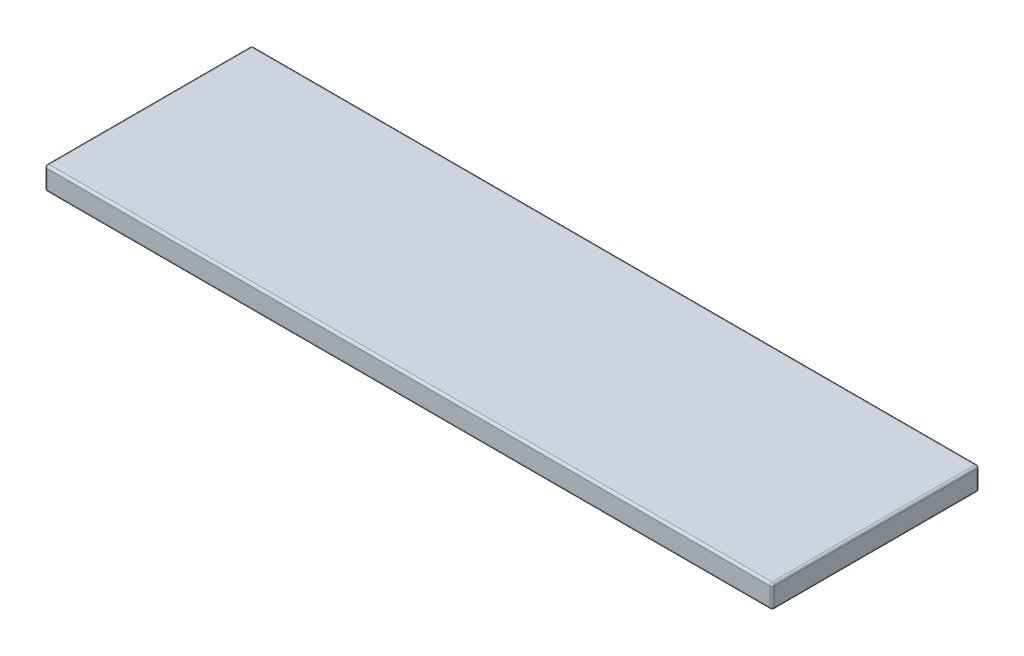
SolidWorks part; units mm, degrees
material "Balsa"
ref_plane "Plano frontal" through (0, 0, 0) normal (0, 0, 1) x (1, 0, 0)
ref_plane "Plano superior" through (0, 0, 0) normal (0, 1, 0) x (1, 0, 0)
ref_plane "Plano direito" through (0, 0, 0) normal (1, 0, 0) x (0, 0, -1)
sketch "Esboço1" plane through (0, 0, 0) normal (0, 1, 0) x (1, 0, 0)
  line L1 (-79, -22.5) -> (79, -22.5)
  line L2 (-79, -22.5) -> (-79, 22.5)
  line L3 (-79, 22.5) -> (79, 22.5)
  line L4 (79, -22.5) -> (79, 22.5)
  line L5 (-79, -22.5) -> (79, 22.5) construction
  line L6 (-79, 22.5) -> (79, -22.5) construction
  point P0 (0, 0)
  dimension "D1" = 158
  dimension "D2" = 45
extrude "Ressalto-extrusão1" add sketch "Esboço1" along normal blind 5
fillet "Filete1" radius 0.5 12 edges at (79, 2.5, -22.5) (-79, 2.5, -22.5) (-79, 2.5, 22.5) (79, 2.5, 22.5) (0, 5, 22.5) (-79, 5, 0) (0, 5, -22.5) (79, 5, 0) (0, 0, -22.5) (-79, 0, 0) (0, 0, 22.5) (79, 0, 0)
